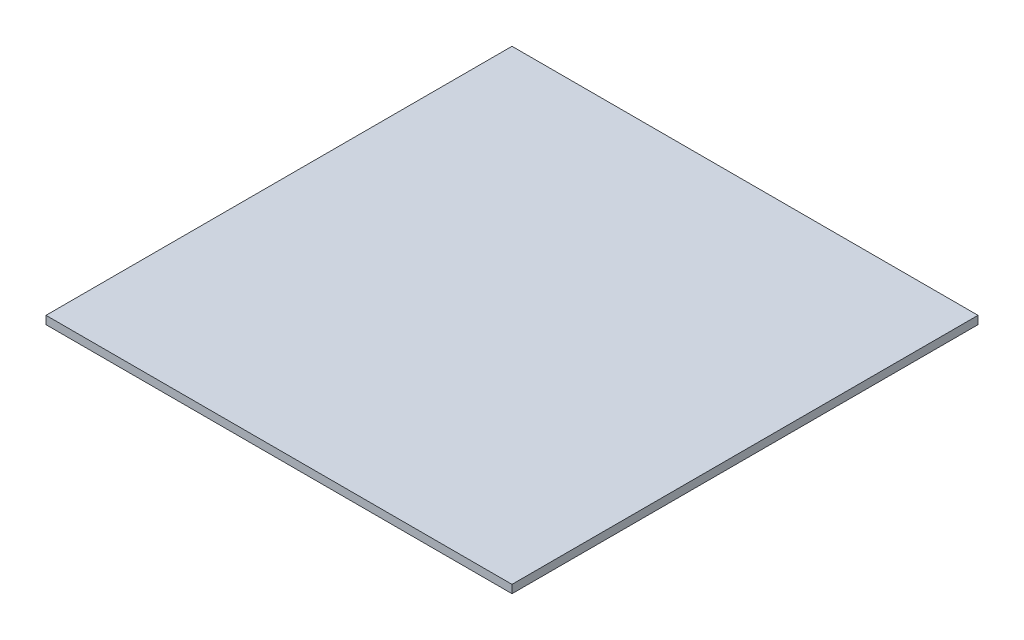
SolidWorks part; units mm, degrees
ref_plane "Front Plane" through (0, 0, 0) normal (0, 0, 1) x (1, 0, 0)
ref_plane "Top Plane" through (0, 0, 0) normal (0, 1, 0) x (1, 0, 0)
ref_plane "Right Plane" through (0, 0, 0) normal (1, 0, 0) x (0, 0, -1)
sketch "Sketch1" plane through (0, 0, 0) normal (0, 1, 0) x (1, 0, 0)
  line L1 (1064.3505, 4519.8558) -> (204.3505, 4519.8558)
  line L2 (1064.3505, 4519.8558) -> (1064.3505, 3659.8558)
  line L3 (1064.3505, 3659.8558) -> (204.3505, 3659.8558)
  line L4 (204.3505, 4519.8558) -> (204.3505, 3659.8558)
  line L5 (489.3505, 3664.8558) -> (209.3505, 3664.8558) construction
  line L6 (209.3505, 4514.8558) -> (209.3505, 4234.8558) construction
  line L7 (1059.3505, 4514.8558) -> (1059.3505, 4234.8558) construction
  line L8 (1059.3505, 4514.8558) -> (779.3505, 4514.8558) construction
  dimension "D1" = 5
  dimension "D2" = 5
  dimension "D3" = 5
  dimension "D4" = 5
extrude "Boss-Extrude1" add sketch "Sketch1" along normal blind 15
